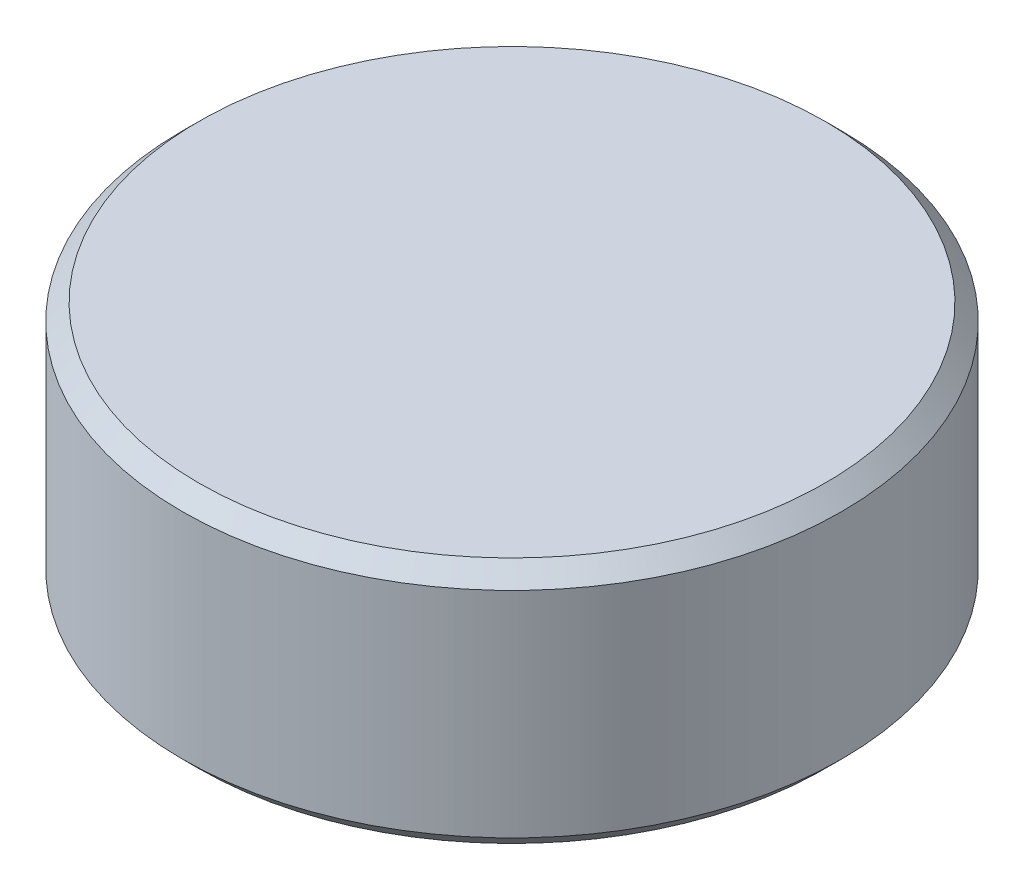
SolidWorks part; units mm, degrees
ref_plane "Front Plane" through (0, 0, 0) normal (0, 0, 1) x (1, 0, 0)
ref_plane "Top Plane" through (0, 0, 0) normal (0, 1, 0) x (1, 0, 0)
ref_plane "Right Plane" through (0, 0, 0) normal (1, 0, 0) x (0, 0, -1)
sketch "Sketch1" plane through (0, 0, 0) normal (0, 1, 0) x (1, 0, 0)
  circle A0 centre (0, 0) radius 2
  dimension "D1" = 4
extrude "Boss-Extrude1" add sketch "Sketch1" along normal blind 1.5
chamfer "Chamfer1" distance 0.1 angle 45 2 edges at (0, 0, 2) (0, 1.5, 2)
